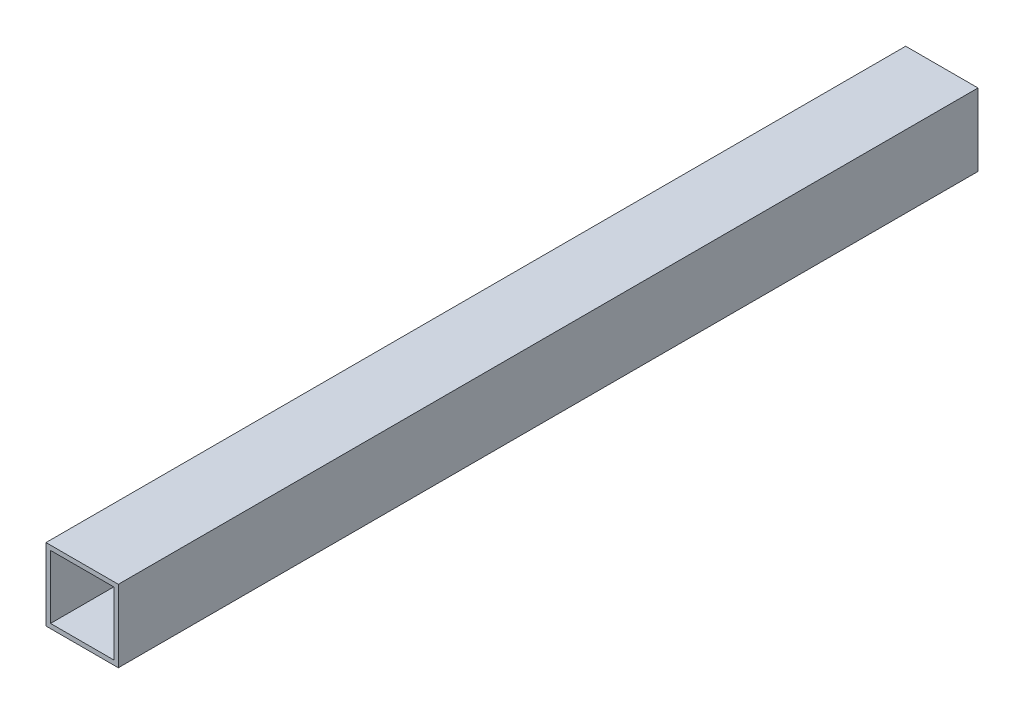
SolidWorks part; units mm, degrees
material "Acrylic (Medium-high impact)"
ref_plane "Front Plane" through (0, 0, 0) normal (0, 0, 1) x (1, 0, 0)
ref_plane "Top Plane" through (0, 0, 0) normal (0, 1, 0) x (1, 0, 0)
ref_plane "Right Plane" through (0, 0, 0) normal (1, 0, 0) x (0, 0, -1)
sketch "Sketch1" plane through (0, 0, 0) normal (0, 0, 1) x (1, 0, 0)
  line L1 (-12.7, -12.7) -> (12.7, -12.7)
  line L2 (-12.7, -12.7) -> (-12.7, 12.7)
  line L3 (-12.7, 12.7) -> (12.7, 12.7)
  line L4 (12.7, -12.7) -> (12.7, 12.7)
  line L5 (-12.7, -12.7) -> (12.7, 12.7) construction
  line L6 (-12.7, 12.7) -> (12.7, -12.7) construction
  line L7 (-11.1125, -11.1125) -> (11.1125, -11.1125)
  line L8 (-11.1125, -11.1125) -> (-11.1125, 11.1125)
  line L9 (-11.1125, 11.1125) -> (11.1125, 11.1125)
  line L10 (11.1125, -11.1125) -> (11.1125, 11.1125)
  line L11 (-11.1125, -11.1125) -> (11.1125, 11.1125) construction
  line L12 (-11.1125, 11.1125) -> (11.1125, -11.1125) construction
  point P0 (0, 0)
  point P6 (0, 0)
  dimension "D1" = 1.5875
  dimension "D2" = 25.4
extrude "Boss-Extrude1" add sketch "Sketch1" along normal mid plane 301.9397
